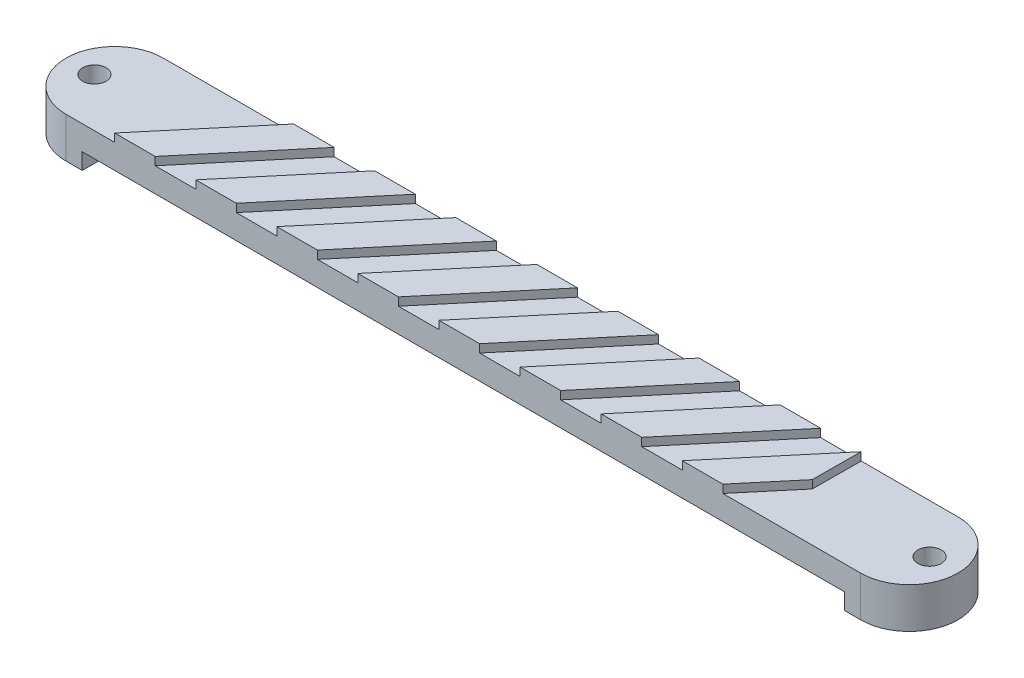
SolidWorks part; units mm, degrees
ref_plane "Front Plane" through (0, 0, 0) normal (0, 0, 1) x (1, 0, 0)
ref_plane "Top Plane" through (0, 0, 0) normal (0, 1, 0) x (1, 0, 0)
ref_plane "Right Plane" through (0, 0, 0) normal (1, 0, 0) x (0, 0, -1)
sketch "Sketch1" plane through (0, 0, 0) normal (0, 1, 0) x (1, 0, 0)
  line L0 (-49, 0) -> (49, 0) construction
  line L1 (-49, 6) -> (49, 6)
  line L2 (-49, -6) -> (49, -6)
  arc A0 (-49, 6) -> (-49, -6) centre (-49, 0) ccw
  arc A1 (49, -6) -> (49, 6) centre (49, 0) ccw
  circle A2 centre (-51.5, 0) radius 1.45
  circle A3 centre (51.5, 0) radius 1.45
  point P2 (0, 0)
  point P12 (-55, 0)
  point P13 (55, 0)
  dimension "D3" = 2.9
  dimension "D4" = 3.5
  dimension "D1" = 110
  dimension "D2" = 12
  dimension "D5" = 3.5
extrude "Boss-Extrude1" add sketch "Sketch1" along normal blind 3 contours L2 A1 L1 A0 | A2 | A3
sketch "Sketch2" plane through (0, 0, 0) normal (0, -1, 0) x (1, 0, 0)
  line L0 (-49, 6) -> (49, 6) construction
  line L1 (53.0877, -2.75) -> (54.6754, 0)
  line L2 (54.6754, 0) -> (53.0877, 2.75)
  line L3 (53.0877, 2.75) -> (49.9123, 2.75)
  line L4 (49.9123, 2.75) -> (48.3246, 0)
  line L5 (48.3246, 0) -> (49.9123, -2.75)
  line L6 (49.9123, -2.75) -> (53.0877, -2.75)
  line L7 (47, 6) -> (47, -6)
  line L8 (-49, -6) -> (49, -6) construction
  line L9 (47, -6) -> (49, -6)
  line L10 (49, 6) -> (47, 6)
  line L11 (0, 0) -> (0, -50000) construction
  line L12 (-49, 6) -> (-47, 6)
  line L13 (-47, -6) -> (-49, -6)
  line L14 (-47, 6) -> (-47, -6)
  line L15 (-49.9123, -2.75) -> (-53.0877, -2.75)
  line L16 (-48.3246, 0) -> (-49.9123, -2.75)
  line L17 (-49.9123, 2.75) -> (-48.3246, 0)
  line L18 (-53.0877, 2.75) -> (-49.9123, 2.75)
  line L19 (-54.6754, 0) -> (-53.0877, 2.75)
  line L20 (-53.0877, -2.75) -> (-54.6754, 0)
  circle A5 centre (51.5, 0) radius 1.45 construction
  circle A6 centre (51.5, 0) radius 1.45
  circle A7 centre (51.5, 0) radius 2.75 construction
  arc A8 (49, -6) -> (49, 6) centre (49, 0) ccw
  circle A9 centre (-51.5, 0) radius 2.75 construction
  arc A10 (-49, -6) -> (-49, 6) centre (-49, 0) cw
  circle A11 centre (-51.5, 0) radius 1.45
  arc M4 (-49, 6) -> (-49, -6) centre (-49, 0) ccw
  line M5 (-49, -6) -> (49, -6)
  arc M6 (49, -6) -> (49, 6) centre (49, 0) ccw
  line M7 (49, 6) -> (-49, 6)
  dimension "D1" = 5.5
  dimension "D3" = 2
extrude "Boss-Extrude2" add sketch "Sketch2" along normal blind 2 contours L7 L6 L5 L4 L3 L2 L1 M7 M5 M6 | L14 L15 L20 L19 L18 L17 L16 M7 M4 M5
sketch "Sketch3" plane through (0, 3, 0) normal (0, 1, 0) x (1, 0, 0)
  line L0 (-32.9308, 6) -> (-43, -6)
  line L1 (-49, 6) -> (49, 6) construction
  line L2 (-49, -6) -> (49, -6) construction
  line L3 (-43, -6) -> (-38, -6)
  line L4 (-38, -6) -> (-27.9308, 6)
  line L5 (-27.9308, 6) -> (-32.9308, 6)
  line L6 (-17.9308, 6) -> (-22.9308, 6)
  line L7 (-22.9308, 6) -> (-33, -6)
  line L8 (-33, -6) -> (-28, -6)
  line L9 (-28, -6) -> (-17.9308, 6)
  line L10 (-7.9308, 6) -> (-12.9308, 6)
  line L11 (-12.9308, 6) -> (-23, -6)
  line L12 (-23, -6) -> (-18, -6)
  line L13 (-18, -6) -> (-7.9308, 6)
  line L14 (2.0692, 6) -> (-2.9308, 6)
  line L15 (-2.9308, 6) -> (-13, -6)
  line L16 (-13, -6) -> (-8, -6)
  line L17 (-8, -6) -> (2.0692, 6)
  line L18 (12.0692, 6) -> (7.0692, 6)
  line L19 (7.0692, 6) -> (-3, -6)
  line L20 (-3, -6) -> (2, -6)
  line L21 (2, -6) -> (12.0692, 6)
  line L22 (22.0692, 6) -> (17.0692, 6)
  line L23 (17.0692, 6) -> (7, -6)
  line L24 (7, -6) -> (12, -6)
  line L25 (12, -6) -> (22.0692, 6)
  line L26 (32.0692, 6) -> (27.0692, 6)
  line L27 (27.0692, 6) -> (17, -6)
  line L28 (17, -6) -> (22, -6)
  line L29 (22, -6) -> (32.0692, 6)
  line L31 (37.0692, 6) -> (27, -6)
  line L32 (27, -6) -> (32, -6)
  line L33 (32, -6) -> (37.0346, 0)
  line L34 (37.0692, 6) -> (37.0346, 0)
  line L36 (42.0692, 6) -> (37.0692, 6) [skipped]
  arc A0 (-49, 6) -> (-49, -6) centre (-49, 0) ccw construction
  point P39 (-55, 0)
  dimension "D1" = 5
  dimension "D2" = 50
  dimension "D4" = 12
  dimension "D3" = 8
extrude "Boss-Extrude3" add sketch "Sketch3" along normal blind 1
